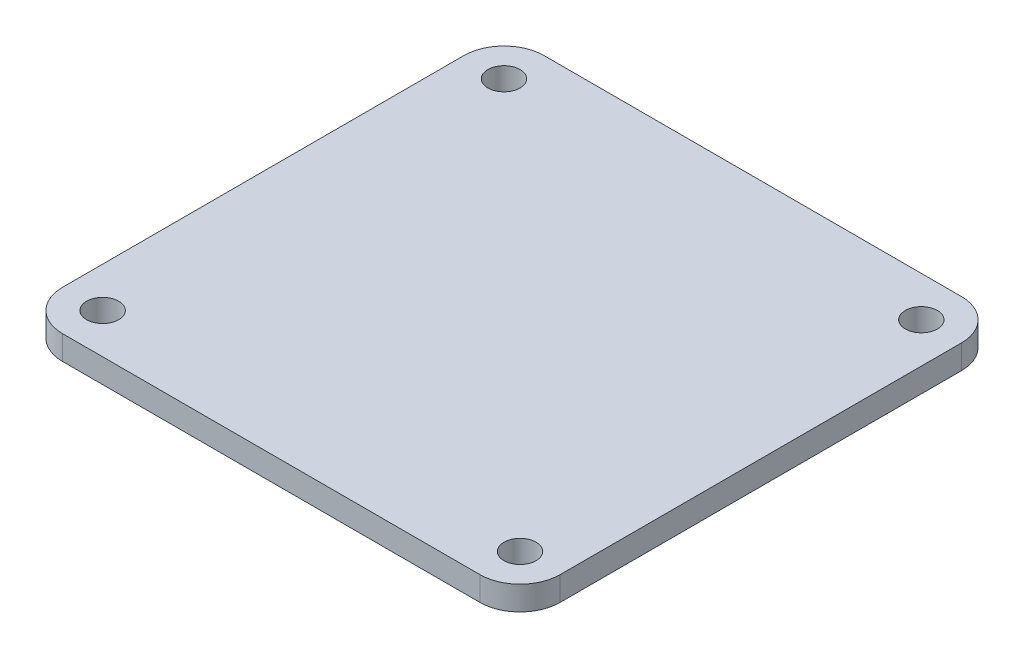
SolidWorks part; units mm, degrees
material "ABS PC"
ref_plane "Front Plane" through (0, 0, 0) normal (0, 0, 1) x (1, 0, 0)
ref_plane "Top Plane" through (0, 0, 0) normal (0, 1, 0) x (1, 0, 0)
ref_plane "Right Plane" through (0, 0, 0) normal (1, 0, 0) x (0, 0, -1)
sketch "Sketch1" plane through (0, 0, 0) normal (0, 1, 0) x (1, 0, 0)
  line L1 (-31, -30) -> (31, -30)
  line L2 (-31, -30) -> (-31, 30)
  line L3 (-31, 30) -> (31, 30)
  line L4 (31, -30) -> (31, 30)
  line L5 (-31, -30) -> (31, 30) construction
  line L6 (-31, 30) -> (31, -30) construction
  point P0 (0, 0)
  dimension "D1" = 60
  dimension "D2" = 62
extrude "Boss-Extrude1" add sketch "Sketch1" along normal blind 3
hole_wizard "Ø4.0 (4) Diameter Hole1" positions "Sketch2" profile "Sketch3" hole size "Ø4.0" standard "ANSI Metric" end condition through all
sketch "Sketch2" plane through (0, 3, 0) normal (0, 1, 0) x (1, 0, 0)
  line L1 (26, -25) -> (-26, -25)
  line L2 (26, -25) -> (26, 25)
  line L3 (26, 25) -> (-26, 25)
  line L4 (-26, -25) -> (-26, 25)
  line L5 (26, -25) -> (-26, 25) construction
  line L6 (26, 25) -> (-26, -25) construction
  line L7 (0, 30) -> (0, 0) construction
  line L8 (31, 30) -> (-31, 30) construction
  line L9 (0, 0) -> (0, -30) construction
  line L10 (-31, -30) -> (31, -30) construction
  line L12 (-31, 0) -> (0, 0) construction
  line L13 (-31, 30) -> (-31, -30) construction
  line L14 (0, 0) -> (31, 0) construction
  line L15 (31, -30) -> (31, 30) construction
  point P1 (-26, 25)
  point P4 (26, -25)
  point P5 (26, 25)
  point P6 (-26, -25)
  dimension "D1" = 52
  dimension "D2" = 50
sketch "Sketch3" plane through (-26, 3, -25) normal (1, 0, 0) x (0, 0, 1)
  line L0 (0, 0) -> (0, 3)
  line L1 (0, 3) -> (2, 3)
  line L2 (2, 3) -> (2, 0)
  line L5 (2, 0) -> (0, 0)
  line L11 (0, -6.35) -> (0, 107.95) construction
  dimension "Thru Hole Dia." = 4
  dimension "Thru Hole Depth" = 3
fillet "Fillet1" radius 5 4 edges at (31, 1.5, 30) (-31, 1.5, 30) (31, 1.5, -30) (-31, 1.5, -30)
